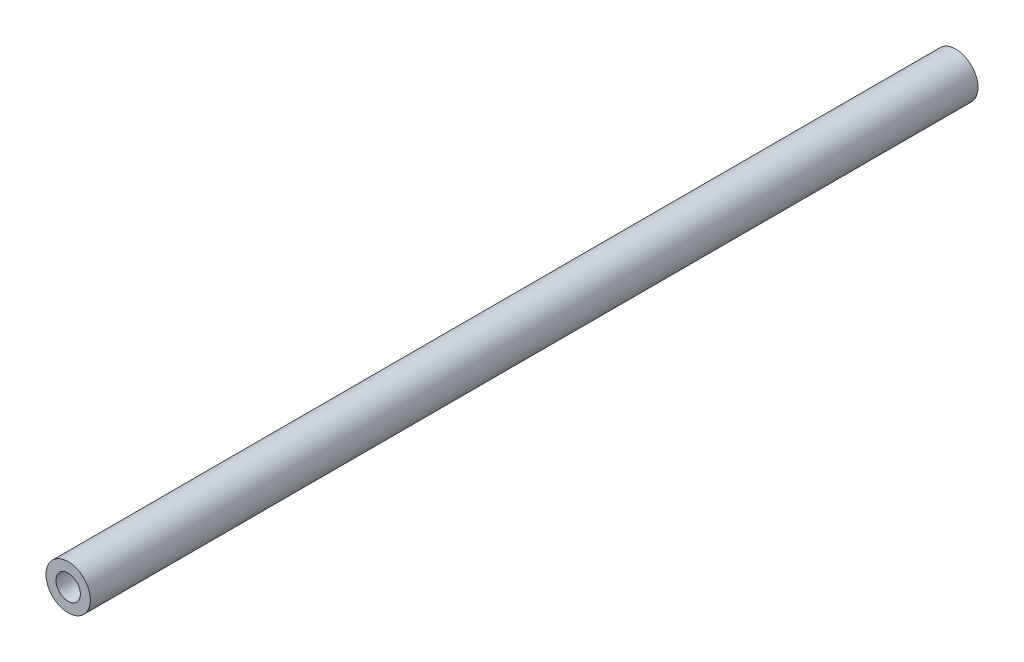
SolidWorks part; units mm, degrees
ref_plane "Front Plane" through (0, 0, 0) normal (0, 0, 1) x (1, 0, 0)
ref_plane "Top Plane" through (0, 0, 0) normal (0, 1, 0) x (1, 0, 0)
ref_plane "Right Plane" through (0, 0, 0) normal (1, 0, 0) x (0, 0, -1)
sketch "Sketch1" plane through (0, 0, 0) normal (0, 0, 1) x (1, 0, 0)
  circle A0 centre (0, 0) radius 3
  dimension "D1" = 6
extrude "Boss-Extrude1" add sketch "Sketch1" along normal blind 120
ref_plane "Plane1" through (0, 0, 60) normal (0, 0, 1) x (1, 0, 0)
sketch "Sketch4" plane through (0, 0, 120) normal (0, 0, 1) x (1, 0, 0)
  point P1 (0, 0)
hole_wizard "M4x0.7 Tapped Hole1" positions "Sketch4" profile "Sketch3" tap size "M4x0.7" standard "ANSI Metric"
sketch "Sketch3" plane through (0, 0, 120) normal (1, 0, 0) x (0, -1, 0)
  line L0 (0, 0) -> (0, 10.9914)
  line L1 (0, 10.9914) -> (1.65, 10)
  line L2 (1.65, 10) -> (1.65, 0)
  line L5 (1.65, 0) -> (0, 0)
  line L10 (0, 10.9914) -> (-1.65, 10) construction
  line L11 (0, -6.35) -> (0, 107.95) construction
  dimension "Tap Drill Dia." = 3.3
  dimension "Tap Drill Depth" = 10
  dimension "Drill Angle" = 118
mirror "Mirror1" about plane through (0, 0, 60) normal (0, 0, 1) of "M4x0.7 Tapped Hole1"
